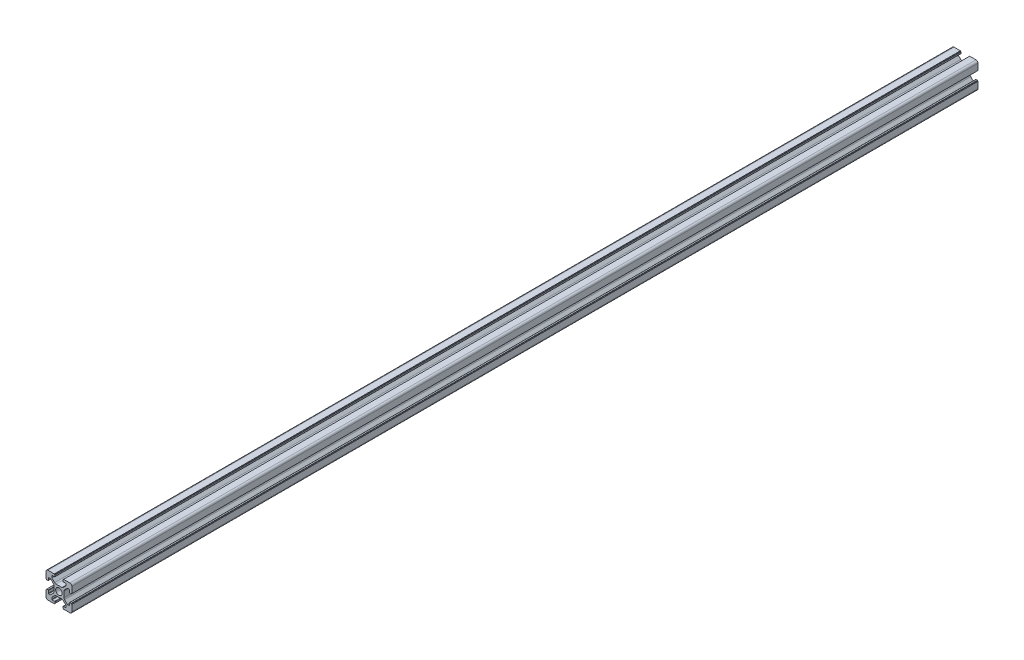
SolidWorks part; units mm, degrees
ref_plane "前视基准面" through (0, 0, 0) normal (0, 0, 1) x (1, 0, 0)
ref_plane "上视基准面" through (0, 0, 0) normal (0, 1, 0) x (1, 0, 0)
ref_plane "右视基准面" through (0, 0, 0) normal (1, 0, 0) x (0, 0, -1)
sketch "草图1" plane through (0, 0, 0) normal (0, 0, 1) x (1, 0, 0)
  line L0 (4.216, 3.2442) -> (6.4367, 5.4649)
  line L1 (6.4367, 5.4649) -> (7.7767, 5.4649)
  line L2 (8.0767, 5.1649) -> (8.0767, 3.3649)
  line L3 (8.3767, 3.0649) -> (9.3767, 3.0649)
  line L4 (9.3767, 3.0649) -> (9.3767, 3.3649)
  line L5 (9.5767, 3.5649) -> (9.8767, 3.5649)
  line L6 (9.8767, 3.5649) -> (9.8767, 8.4649)
  line L7 (8.3767, 9.9649) -> (3.4767, 9.9649)
  line L8 (3.4767, 9.9649) -> (3.4767, 9.6649)
  line L9 (3.2767, 9.4649) -> (2.9767, 9.4649)
  line L10 (2.9767, 9.4649) -> (2.9767, 8.4649)
  line L11 (3.2767, 8.1649) -> (5.0767, 8.1649)
  line L12 (5.3767, 7.8649) -> (5.3767, 6.5249)
  line L13 (5.3767, 6.5249) -> (3.156, 4.3042)
  line L14 (2.0953, 3.8649) -> (-2.342, 3.8649)
  line L15 (-3.4027, 4.3042) -> (-5.6233, 6.5249)
  line L16 (-5.6233, 6.5249) -> (-5.6233, 7.8649)
  line L17 (-5.3233, 8.1649) -> (-3.5233, 8.1649)
  line L18 (-3.2233, 8.4649) -> (-3.2233, 9.4649)
  line L19 (-3.2233, 9.4649) -> (-3.5233, 9.4649)
  line L20 (-3.7233, 9.6649) -> (-3.7233, 9.9649)
  line L21 (-3.7233, 9.9649) -> (-8.6233, 9.9649)
  line L22 (-10.1233, 8.4649) -> (-10.1233, 3.5649)
  line L23 (-10.1233, 3.5649) -> (-9.8233, 3.5649)
  line L24 (-9.6233, 3.3649) -> (-9.6233, 3.0649)
  line L25 (-9.6233, 3.0649) -> (-8.6233, 3.0649)
  line L26 (-8.3233, 3.3649) -> (-8.3233, 5.1649)
  line L27 (-8.0233, 5.4649) -> (-6.6833, 5.4649)
  line L28 (-6.6833, 5.4649) -> (-4.4627, 3.2442)
  line L29 (-4.0233, 2.1836) -> (-4.0233, -2.2538)
  line L30 (-4.4627, -3.3144) -> (-6.6833, -5.5351)
  line L31 (-6.6833, -5.5351) -> (-8.0233, -5.5351)
  line L32 (-8.3233, -5.2351) -> (-8.3233, -3.4351)
  line L33 (-8.6233, -3.1351) -> (-9.6233, -3.1351)
  line L34 (-9.6233, -3.1351) -> (-9.6233, -3.4351)
  line L35 (-9.8233, -3.6351) -> (-10.1233, -3.6351)
  line L36 (-10.1233, -3.6351) -> (-10.1233, -8.5351)
  line L37 (-8.6233, -10.0351) -> (-3.7233, -10.0351)
  line L38 (-3.7233, -10.0351) -> (-3.7233, -9.7351)
  line L39 (-3.5233, -9.5351) -> (-3.2233, -9.5351)
  line L40 (-3.2233, -9.5351) -> (-3.2233, -8.5351)
  line L41 (-3.5233, -8.2351) -> (-5.3233, -8.2351)
  line L42 (-5.6233, -7.9351) -> (-5.6233, -6.5951)
  line L43 (-5.6233, -6.5951) -> (-3.4027, -4.3744)
  line L44 (-2.342, -3.9351) -> (2.0953, -3.9351)
  line L45 (3.156, -4.3744) -> (5.3767, -6.5951)
  line L46 (5.3767, -6.5951) -> (5.3767, -7.9351)
  line L47 (5.0767, -8.2351) -> (3.2767, -8.2351)
  line L48 (2.9767, -8.5351) -> (2.9767, -9.5351)
  line L49 (2.9767, -9.5351) -> (3.2767, -9.5351)
  line L50 (3.4767, -9.7351) -> (3.4767, -10.0351)
  line L51 (3.4767, -10.0351) -> (8.3767, -10.0351)
  line L52 (9.8767, -8.5351) -> (9.8767, -3.6351)
  line L53 (9.8767, -3.6351) -> (9.5767, -3.6351)
  line L54 (9.3767, -3.4351) -> (9.3767, -3.1351)
  line L55 (9.3767, -3.1351) -> (8.3767, -3.1351)
  line L56 (8.0767, -3.4351) -> (8.0767, -5.2351)
  line L57 (7.7767, -5.5351) -> (6.4367, -5.5351)
  line L58 (6.4367, -5.5351) -> (4.216, -3.3144)
  line L59 (3.7767, -2.2538) -> (3.7767, 2.1836)
  circle A0 centre (-0.1233, -0.0351) radius 2.5
  arc A1 (8.0767, 5.1649) -> (7.7767, 5.4649) centre (7.7767, 5.1649) ccw
  arc A2 (8.0767, 3.3649) -> (8.3767, 3.0649) centre (8.3767, 3.3649) ccw
  arc A3 (9.5767, 3.5649) -> (9.3767, 3.3649) centre (9.5767, 3.3649) ccw
  arc A4 (9.8767, 8.4649) -> (8.3767, 9.9649) centre (8.3767, 8.4649) ccw
  arc A5 (3.2767, 9.4649) -> (3.4767, 9.6649) centre (3.2767, 9.6649) ccw
  arc A6 (2.9767, 8.4649) -> (3.2767, 8.1649) centre (3.2767, 8.4649) ccw
  arc A7 (5.3767, 7.8649) -> (5.0767, 8.1649) centre (5.0767, 7.8649) ccw
  arc A8 (2.0953, 3.8649) -> (3.156, 4.3042) centre (2.0953, 5.3649) ccw
  arc A9 (-3.4027, 4.3042) -> (-2.342, 3.8649) centre (-2.342, 5.3649) ccw
  arc A10 (-5.3233, 8.1649) -> (-5.6233, 7.8649) centre (-5.3233, 7.8649) ccw
  arc A11 (-3.5233, 8.1649) -> (-3.2233, 8.4649) centre (-3.5233, 8.4649) ccw
  arc A12 (-3.7233, 9.6649) -> (-3.5233, 9.4649) centre (-3.5233, 9.6649) ccw
  arc A13 (-8.6233, 9.9649) -> (-10.1233, 8.4649) centre (-8.6233, 8.4649) ccw
  arc A14 (-9.6233, 3.3649) -> (-9.8233, 3.5649) centre (-9.8233, 3.3649) ccw
  arc A15 (-8.6233, 3.0649) -> (-8.3233, 3.3649) centre (-8.6233, 3.3649) ccw
  arc A16 (-8.0233, 5.4649) -> (-8.3233, 5.1649) centre (-8.0233, 5.1649) ccw
  arc A17 (-4.0233, 2.1836) -> (-4.4627, 3.2442) centre (-5.5233, 2.1836) ccw
  arc A18 (-4.4627, -3.3144) -> (-4.0233, -2.2538) centre (-5.5233, -2.2538) ccw
  arc A19 (-8.3233, -5.2351) -> (-8.0233, -5.5351) centre (-8.0233, -5.2351) ccw
  arc A20 (-8.3233, -3.4351) -> (-8.6233, -3.1351) centre (-8.6233, -3.4351) ccw
  arc A21 (-9.8233, -3.6351) -> (-9.6233, -3.4351) centre (-9.8233, -3.4351) ccw
  arc A22 (-10.1233, -8.5351) -> (-8.6233, -10.0351) centre (-8.6233, -8.5351) ccw
  arc A23 (-3.5233, -9.5351) -> (-3.7233, -9.7351) centre (-3.5233, -9.7351) ccw
  arc A24 (-3.2233, -8.5351) -> (-3.5233, -8.2351) centre (-3.5233, -8.5351) ccw
  arc A25 (-5.6233, -7.9351) -> (-5.3233, -8.2351) centre (-5.3233, -7.9351) ccw
  arc A26 (-2.342, -3.9351) -> (-3.4027, -4.3744) centre (-2.342, -5.4351) ccw
  arc A27 (3.156, -4.3744) -> (2.0953, -3.9351) centre (2.0953, -5.4351) ccw
  arc A28 (5.0767, -8.2351) -> (5.3767, -7.9351) centre (5.0767, -7.9351) ccw
  arc A29 (3.2767, -8.2351) -> (2.9767, -8.5351) centre (3.2767, -8.5351) ccw
  arc A30 (3.4767, -9.7351) -> (3.2767, -9.5351) centre (3.2767, -9.7351) ccw
  arc A31 (8.3767, -10.0351) -> (9.8767, -8.5351) centre (8.3767, -8.5351) ccw
  arc A32 (9.3767, -3.4351) -> (9.5767, -3.6351) centre (9.5767, -3.4351) ccw
  arc A33 (8.3767, -3.1351) -> (8.0767, -3.4351) centre (8.3767, -3.4351) ccw
  arc A34 (7.7767, -5.5351) -> (8.0767, -5.2351) centre (7.7767, -5.2351) ccw
  arc A35 (3.7767, -2.2538) -> (4.216, -3.3144) centre (5.2767, -2.2538) ccw
  arc A36 (4.216, 3.2442) -> (3.7767, 2.1836) centre (5.2767, 2.1836) ccw
extrude "凸台-拉伸1" add sketch "草图1" along normal blind 700
